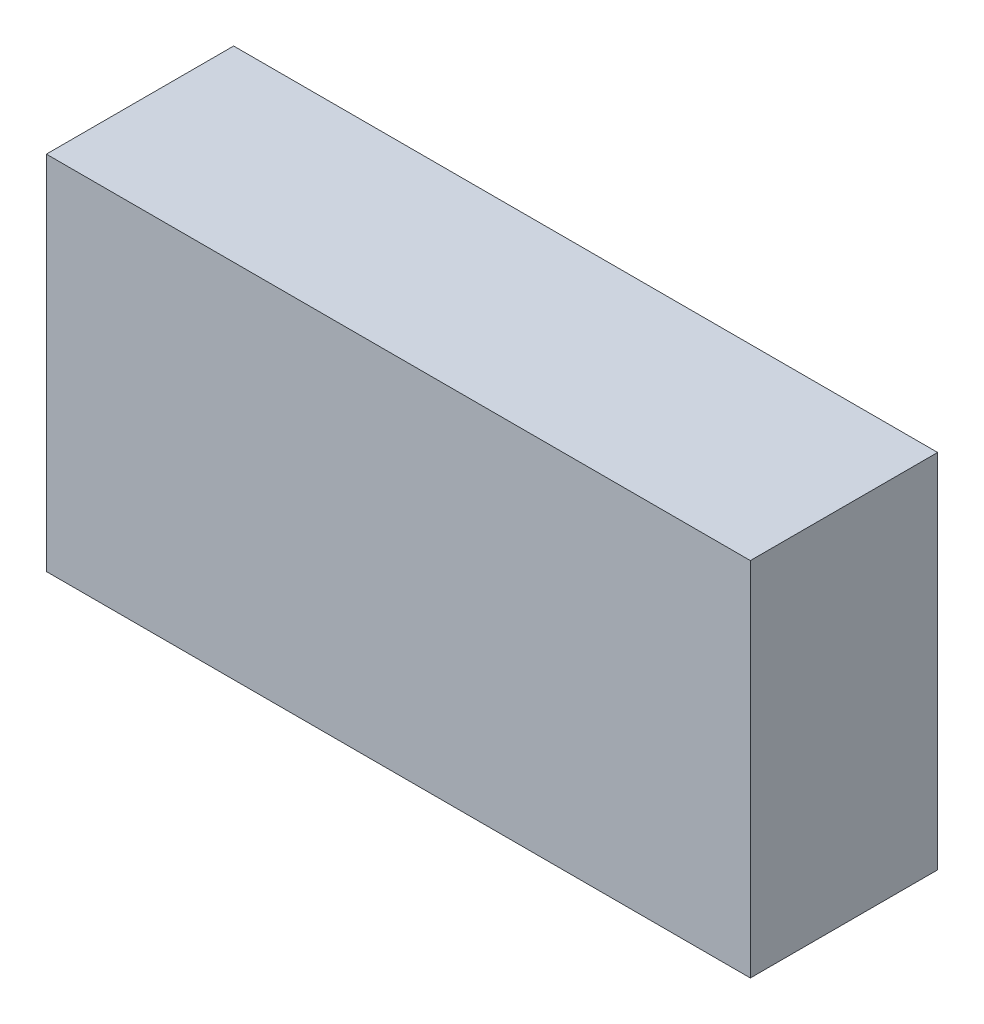
SolidWorks part; units mm, degrees
ref_plane "Front Plane" through (0, 0, 0) normal (0, 0, 1) x (1, 0, 0)
ref_plane "Top Plane" through (0, 0, 0) normal (0, 1, 0) x (1, 0, 0)
ref_plane "Right Plane" through (0, 0, 0) normal (1, 0, 0) x (0, 0, -1)
sketch "Sketch1" plane through (0, 0, 0) normal (0, 0, 1) x (1, 0, 0)
  line L0 (-2.2352, 0.9652) -> (1.524, 0.9652)
  line L1 (1.524, 0.9652) -> (1.524, -0.9652)
  line L2 (1.524, -0.9652) -> (-2.2352, -0.9652)
  line L3 (-2.2352, -0.9652) -> (-2.2352, 0.9652)
extrude "Component_Outline" add sketch "Sketch1" along normal blind 1 separate body
sketch3d "3DSketch1"
  line L0 (0, 0, 0) -> (1, 0, 0)
  line L1 (0, 0, 0) -> (0, 1, 0)
  line L2 (0, 0, 0) -> (0, 0, 1)
  point P0 (0, 0, 0)
